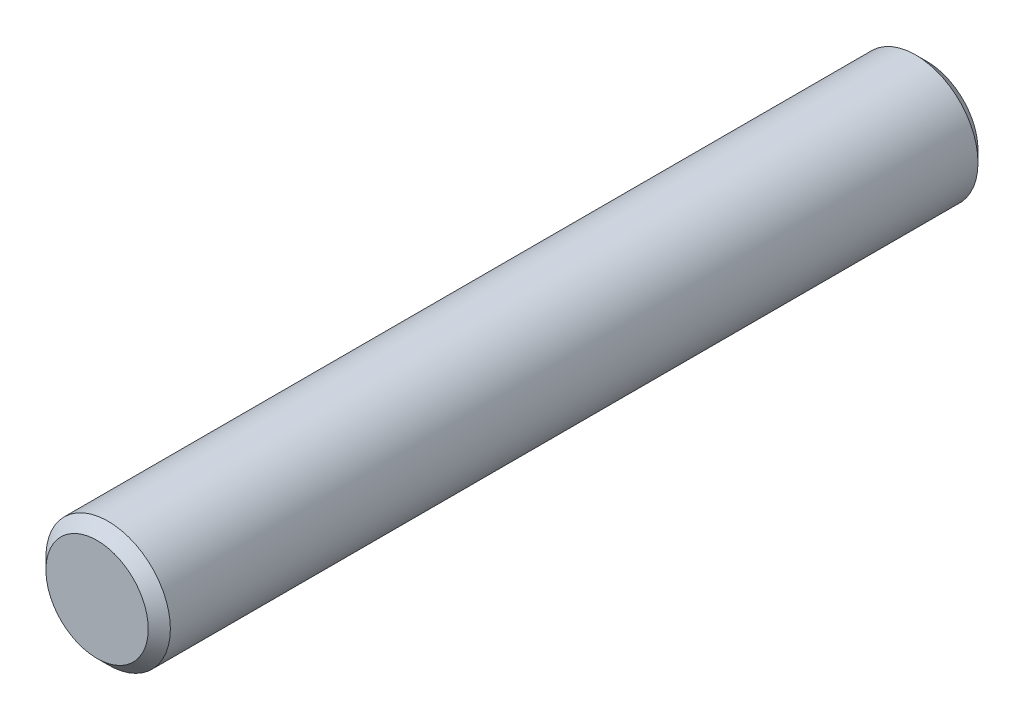
SolidWorks part; units mm, degrees
ref_plane "Front Plane" through (0, 0, 0) normal (0, 0, 1) x (1, 0, 0)
ref_plane "Top Plane" through (0, 0, 0) normal (0, 1, 0) x (1, 0, 0)
ref_plane "Right Plane" through (0, 0, 0) normal (1, 0, 0) x (0, 0, -1)
sketch "Sketch1" plane through (0, 0, 0) normal (0, 0, 1) x (1, 0, 0)
  circle A0 centre (0, 0) radius 4.5
  dimension "D1" = 9
extrude "Boss-Extrude1" add sketch "Sketch1" along normal blind 60
chamfer "Chamfer1" distance 0.8 angle 45 2 edges at (4.5, 0, 0) (4.5, 0, 60)
